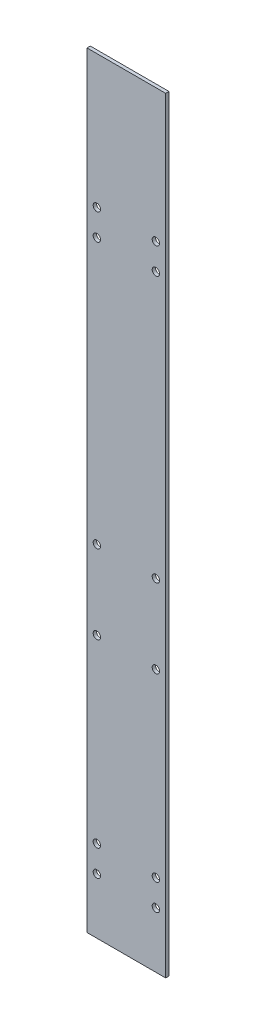
SolidWorks part; units mm, degrees
material "6061-T6 (SS)"
ref_plane "Front Plane" through (0, 0, 0) normal (0, 0, 1) x (1, 0, 0)
ref_plane "Top Plane" through (0, 0, 0) normal (0, 1, 0) x (1, 0, 0)
ref_plane "Right Plane" through (0, 0, 0) normal (1, 0, 0) x (0, 0, -1)
sketch "Sketch1" plane through (0, 0, 0) normal (0, 0, 1) x (1, 0, 0)
  line L0 (469.8805, 5935.98) -> (-469.8805, 5935.98) construction
  line L1 (-325.12, 5935.98) -> (-401.32, 5935.98)
  line L2 (-325.12, 5935.98) -> (-325.12, 5194.3)
  line L3 (-325.12, 5194.3) -> (-401.32, 5194.3)
  line L4 (-401.32, 5935.98) -> (-401.32, 5194.3)
  line L5 (-444.6224, 5194.3) -> (444.6224, 5194.3) construction
  line L6 (-325.12, 5935.98) -> (-325.12, 5194.3) construction
  dimension "D1" = 76.2
extrude "Boss-Extrude1" add sketch "Sketch1" along normal blind 3.175
hole_wizard "1/4 Clearance Hole1" positions "Sketch2" profile "Sketch3" hole size "1/4" standard "ANSI Inch"
sketch "Sketch2" plane through (0, 0, 3.175) normal (0, 0, 1) x (1, 0, 0)
  line L0 (0, 5935.98) -> (0, 5194.3) construction
  point P0 (-391.795, 5248.275)
  point P3 (-391.795, 5273.675)
  point P6 (-334.645, 5273.675)
  point P9 (-334.645, 5248.275)
  point P12 (-334.645, 5781.675)
  point P15 (-334.645, 5807.075)
  point P18 (-391.795, 5807.075)
  point P21 (-391.795, 5781.675)
  point P25 (-391.795, 5448.3)
  point P27 (-334.645, 5448.3)
  point P35 (-391.795, 5524.5)
  point P37 (-334.645, 5524.5)
  point P54 (334.645, 5524.5)
  point P55 (391.795, 5524.5)
  point P56 (334.645, 5448.3)
  point P57 (391.795, 5448.3)
  point P58 (391.795, 5781.675)
  point P59 (391.795, 5807.075)
  point P60 (334.645, 5807.075)
  point P61 (334.645, 5781.675)
  point P62 (334.645, 5248.275)
  point P63 (334.645, 5273.675)
  point P64 (391.795, 5273.675)
  point P65 (391.795, 5248.275)
sketch "Sketch3" plane through (-391.795, 5248.275, 3.175) normal (1, 0, 0) x (0, -1, 0)
  line L0 (0, 0) -> (0, 52.9458)
  line L1 (0, 52.9458) -> (3.5712, 50.8)
  line L2 (3.5712, 50.8) -> (3.5712, 0)
  line L3 (3.5712, 0) -> (0, 0)
  line L4 (0, 52.9458) -> (-3.5712, 50.8) construction
  line L5 (0, -6.35) -> (0, 107.95) construction
  dimension "Hole Dia." = 7.1425
  dimension "Hole Depth" = 50.8
  dimension "Drill Angle" = 118
